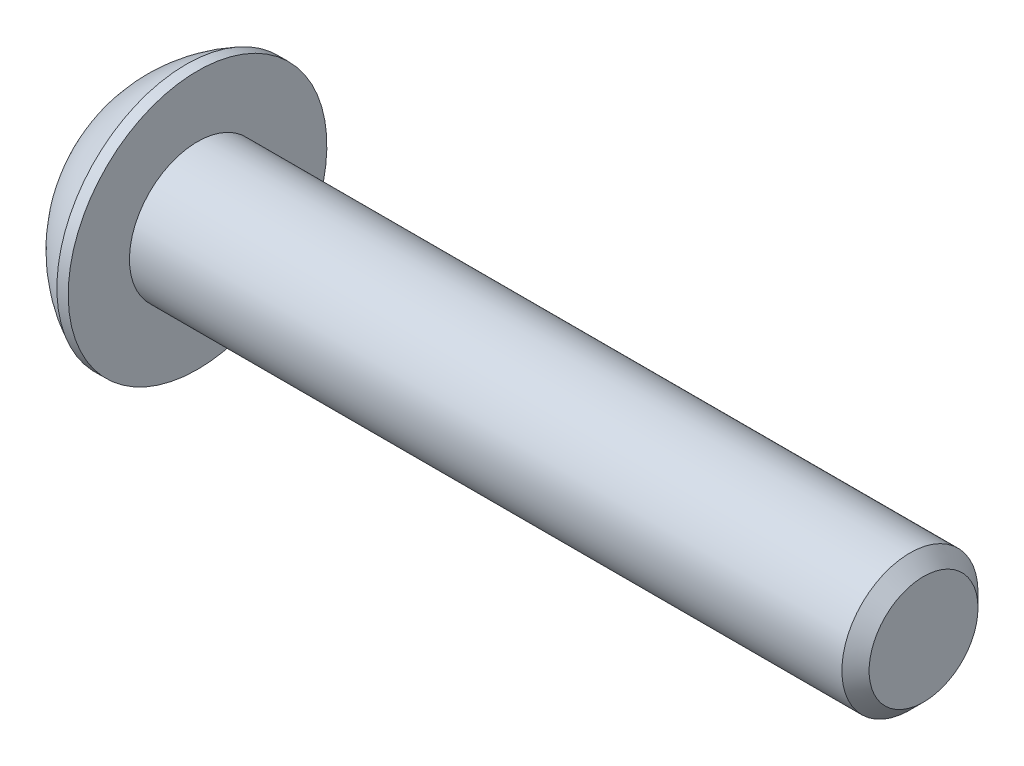
SolidWorks part; units mm, degrees
material "Plain Carbon Steel"
ref_plane "Front Plane" through (0, 0, 0) normal (0, 0, 1) x (1, 0, 0)
ref_plane "Top Plane" through (0, 0, 0) normal (0, 1, 0) x (1, 0, 0)
ref_plane "Right Plane" through (0, 0, 0) normal (1, 0, 0) x (0, 0, -1)
sketch "Sketch2" plane through (0, 0, 0) normal (1, 0, 0) x (0, 0, -1)
  circle A0 centre (0, 0) radius 1.5
  dimension "D1" = 3
extrude "Boss-Extrude1" add sketch "Sketch2" against normal blind 16
chamfer "Chamfer1" distance 0.3 angle 45 1 edges at (0, 0, -1.5)
sketch "Sketch6" plane through (0, 0, 0) normal (0, 0, 1) x (1, 0, 0)
  line L0 (-17.65, 0) -> (-17.65, 1.5)
  line L1 (-17.65, 0) -> (-16, 0)
  line L2 (-16.25, 2.85) -> (-16, 2.85)
  line L6 (-16, 2.85) -> (-16, 0)
  line L8 (-16, 0) -> (-14.6471, 0) construction
  line L10 (-16, 1.5) -> (-16, -1.5) construction
  arc A0 (-17.65, 1.5) -> (-16.25, 2.85) centre (-14.8527, 0) cw
  dimension "D3" = 0.25
  dimension "D1" = 5.7
  dimension "D2" = 1.65
  dimension "D4" = 3
revolve "Revolve1" add sketch "Sketch6" angle 360 about L8
sketch "Sketch7" plane through (-17.65, 0, 0) normal (-1, 0, 0) x (0, 0, 1)
  line L1 (0, 1.1547) -> (-1, 0.5774)
  line L2 (-1, 0.5774) -> (-1, -0.5774)
  line L3 (-1, -0.5774) -> (0, -1.1547)
  line L4 (0, -1.1547) -> (1, -0.5774)
  line L5 (1, -0.5774) -> (1, 0.5774)
  line L6 (1, 0.5774) -> (0, 1.1547)
  circle A0 centre (0, 0) radius 1 construction
  dimension "D1" = 2
extrude "Cut-Extrude1" cut sketch "Sketch7" against normal blind 1.2
sketch "Sketch8" plane through (-17.65, 0, 0) normal (-1, 0, 0) x (0, 0, 1)
  circle A0 centre (0, 0) radius 1.2047
  dimension "D1" = 0.05
extrude "Cut-Extrude2" cut sketch "Sketch8" against normal blind 1 draft 45
